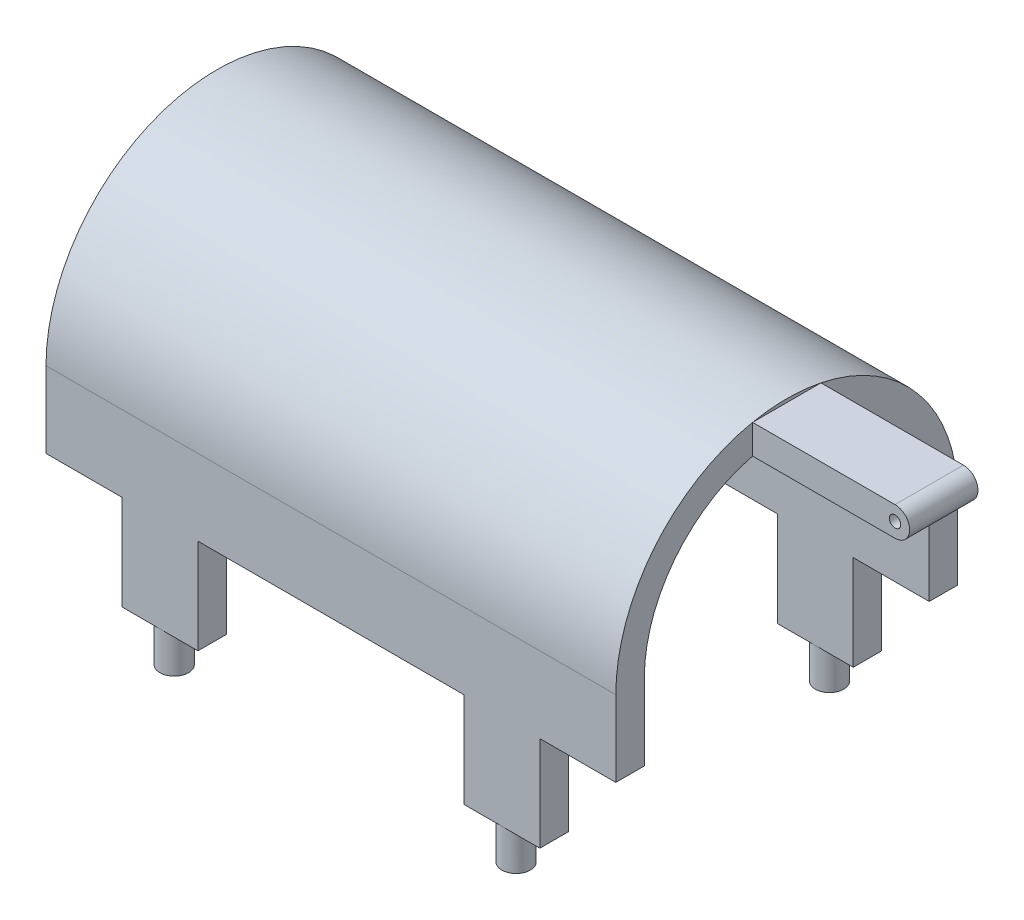
SolidWorks part; units mm, degrees
ref_plane "Front Plane" through (0, 0, 0) normal (0, 0, 1) x (1, 0, 0)
ref_plane "Top Plane" through (0, 0, 0) normal (0, 1, 0) x (1, 0, 0)
ref_plane "Right Plane" through (0, 0, 0) normal (1, 0, 0) x (0, 0, -1)
sketch "Sketch1" plane through (0, 0, 0) normal (1, 0, 0) x (0, 0, -1)
  line L2 (-9.525, 0) -> (-9.525, -11.43)
  line L3 (-9.525, -11.43) -> (-11.43, -11.43)
  line L4 (-11.43, 0) -> (-11.43, -11.43)
  line L6 (9.525, 0) -> (9.525, -11.43)
  line L7 (9.525, -11.43) -> (11.43, -11.43)
  line L8 (11.43, 0) -> (11.43, -11.43)
  arc A0 (9.525, 0) -> (-9.525, 0) centre (0, 0) ccw
  arc A1 (11.43, 0) -> (-11.43, 0) centre (0, 0) ccw
  dimension "D1" = 19.05
  dimension "D2" = 22.86
extrude "Boss-Extrude1" add sketch "Sketch1" along normal mid plane 38.1
sketch "Sketch2" plane through (19.05, 0, 0) normal (1, 0, 0) x (0, 0, -1)
  line L1 (-2.286, 11.1991) -> (2.286, 11.1991)
  line L2 (-2.286, 11.1991) -> (-2.286, 9.2466)
  line L3 (-2.286, 9.2466) -> (2.286, 9.2466)
  line L4 (2.286, 11.1991) -> (2.286, 9.2466)
  arc A0 (11.43, 0) -> (-11.43, 0) centre (0, 0) ccw construction
  arc A1 (9.525, 0) -> (-9.525, 0) centre (0, 0) ccw construction
  point P10 (0, 9.2466)
  dimension "D1" = 4.572
extrude "Boss-Extrude2" add sketch "Sketch2" along normal mid plane 19.05
sketch "Sketch3" plane through (0, 0, -2.286) normal (0, 0, -1) x (-1, 0, 0)
  line L0 (-28.575, 9.2466) -> (-28.575, 11.1991) construction
  circle A0 centre (-28.575, 10.2228) radius 0.9762
extrude "Boss-Extrude3" add sketch "Sketch3" against normal up to surface (4.572 mm away) up to face at (23.8125, 10.2228, 2.286)
sketch "Sketch4" plane through (0, 0, -2.286) normal (0, 0, -1) x (-1, 0, 0)
  circle A0 centre (-28.575, 10.2228) radius 0.381
  arc A1 (-28.575, 11.1991) -> (-28.575, 9.2466) centre (-28.575, 10.2228) ccw construction
  dimension "D1" = 0.762
extrude "Cut-Extrude1" cut sketch "Sketch4" against normal through all
sketch "Sketch5" plane through (0, 0, -11.43) normal (0, 0, -1) x (-1, 0, 0)
  line L0 (-19.05, -11.43) -> (19.05, -11.43) construction
  line L1 (-19.05, -11.43) -> (-13.97, -11.43)
  line L2 (-19.05, -11.43) -> (-19.05, -5.08)
  line L3 (-19.05, -5.08) -> (-13.97, -5.08)
  line L4 (-13.97, -11.43) -> (-13.97, -5.08)
  line L5 (-8.89, -11.43) -> (8.89, -11.43)
  line L6 (-8.89, -11.43) -> (-8.89, -5.08)
  line L7 (-8.89, -5.08) -> (8.89, -5.08)
  line L8 (8.89, -11.43) -> (8.89, -5.08)
  line L10 (19.05, -11.43) -> (13.97, -11.43)
  line L11 (19.05, -11.43) -> (19.05, -5.08)
  line L12 (19.05, -5.08) -> (13.97, -5.08)
  line L13 (13.97, -11.43) -> (13.97, -5.08)
  dimension "D1" = 6.35
  dimension "D2" = 5.08
  dimension "D3" = 5.08
  dimension "D4" = 5.08
  dimension "D5" = 5.08
extrude "Cut-Extrude2" cut sketch "Sketch5" against normal through all
sketch "Sketch6" plane through (0, -11.43, 0) normal (0, -1, 0) x (1, 0, 0)
  line L0 (13.97, -9.525) -> (8.89, -9.525) construction
  line L1 (13.97, -9.525) -> (13.97, -11.43) construction
  line L2 (13.97, -11.43) -> (8.89, -11.43) construction
  line L3 (12.573, 0) -> (-12.573, 0) construction
  line L4 (0, -12.573) -> (0, 12.573) construction
  circle A0 centre (11.43, -10.4775) radius 0.9525
  circle A1 centre (11.43, 10.4775) radius 0.9525
  circle A2 centre (-11.43, 10.4775) radius 0.9525
  circle A3 centre (-11.43, -10.4775) radius 0.9525
  point P2 (0, 0)
  point P3 (12.0718, -12.5693)
  point P6 (11.43, -9.525)
  point P9 (13.97, -10.4775)
extrude "Boss-Extrude4" add sketch "Sketch6" along normal blind 2.54
equation "\"D3@Sketch5\"=\"D2@Sketch5\""
equation "\"D5@Sketch5\"=\"D4@Sketch5\""
